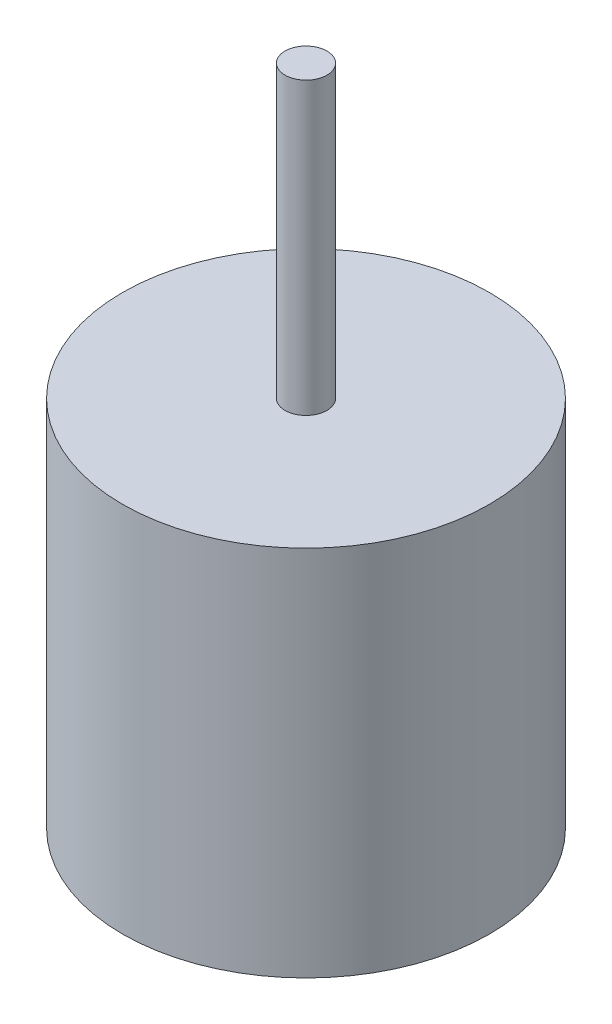
SolidWorks part; units mm, degrees
ref_plane "Front Plane" through (0, 0, 0) normal (0, 0, 1) x (1, 0, 0)
ref_plane "Top Plane" through (0, 0, 0) normal (0, 1, 0) x (1, 0, 0)
ref_plane "Right Plane" through (0, 0, 0) normal (1, 0, 0) x (0, 0, -1)
sketch "Sketch1" plane through (0, 0, 0) normal (0, 1, 0) x (1, 0, 0)
  circle A0 centre (0, 0) radius 13.9
  dimension "D1" = 27.8
extrude "Boss-Extrude1" add sketch "Sketch1" along normal blind 28.2 contours A0
sketch "Sketch2" plane through (0, 28.2, 0) normal (0, 1, 0) x (1, 0, 0)
  circle A0 centre (0, 0) radius 1.585
  dimension "D1" = 3.17
extrude "Boss-Extrude2" add sketch "Sketch2" along normal blind 22
sketch "Sketch3" plane through (0, 0, 0) normal (0, -1, 0) x (1, 0, 0)
  circle A0 centre (0, 0) radius 4.5
  dimension "D1" = 9
extrude "Boss-Extrude3" add sketch "Sketch3" along normal blind 5
